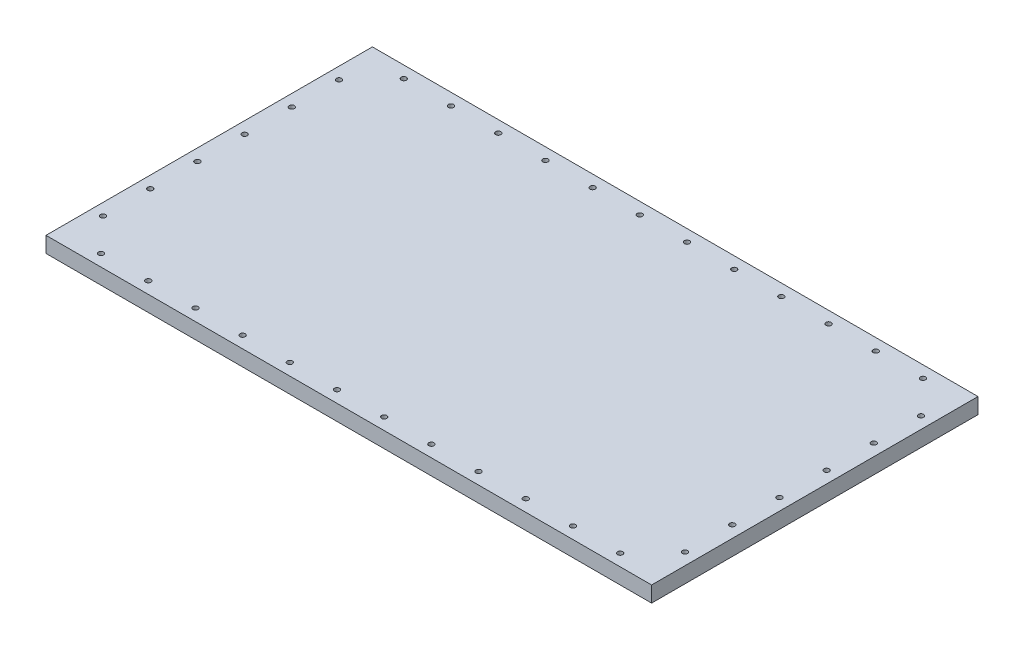
SolidWorks part; units mm, degrees
ref_plane "Front Plane" through (0, 0, 0) normal (0, 0, 1) x (1, 0, 0)
ref_plane "Top Plane" through (0, 0, 0) normal (0, 1, 0) x (1, 0, 0)
ref_plane "Right Plane" through (0, 0, 0) normal (1, 0, 0) x (0, 0, -1)
sketch "Sketch1" plane through (0, 0, 0) normal (0, 0, 1) x (1, 0, 0)
  line L1 (495.3, -12.7) -> (-495.3, -12.7)
  line L2 (495.3, -12.7) -> (495.3, 12.7)
  line L3 (495.3, 12.7) -> (-495.3, 12.7)
  line L4 (-495.3, -12.7) -> (-495.3, 12.7)
  line L5 (495.3, -12.7) -> (-495.3, 12.7) construction
  line L6 (495.3, 12.7) -> (-495.3, -12.7) construction
  line L7 (-495.3, -12.7) -> (-488.95, -12.7)
  line L8 (-495.3, -12.7) -> (-495.3, 12.7)
  line L9 (-495.3, 12.7) -> (-488.95, 12.7)
  line L10 (-488.95, -12.7) -> (-488.95, 12.7)
  line L12 (495.3, -12.7) -> (488.95, -12.7)
  line L13 (495.3, -12.7) -> (495.3, 12.7)
  line L14 (495.3, 12.7) -> (488.95, 12.7)
  line L15 (488.95, -12.7) -> (488.95, 12.7)
  point P0 (0, 0)
  dimension "D1" = 25.4
  dimension "D2" = 990.6
  dimension "D3" = 25.4
  dimension "D4" = 6.35
  dimension "D5" = 6.35
  dimension "D6" = 25.4
extrude "Boss-Extrude1" add sketch "Sketch1" along normal blind 527.05 contours L1 L15 L14 L2 L3 L4 L9 L10
hole_wizard "CSK for 5/16 Flat Head Machine Screw3" positions "Sketch14" profile "Sketch15" countersink size "5/16" standard "ANSI Inch" end condition through all
sketch "Sketch14" plane through (0, -12.7, 0) normal (0, -1, 0) x (-1, 0, 0)
  line L0 (-488.95, -527.05) -> (488.95, -527.05) construction
  line L3 (-488.95, 0) -> (488.95, 0) construction
  line L4 (-488.95, -527.05) -> (-488.95, 0) construction
  line L7 (488.95, -527.05) -> (488.95, 0) construction
  point P0 (419.1, -508)
  point P10 (342.9, -508)
  point P11 (266.7, -508)
  point P12 (190.5, -508)
  point P13 (114.3, -508)
  point P14 (38.1, -508)
  point P15 (-38.1, -508)
  point P16 (-114.3, -508)
  point P17 (-190.5, -508)
  point P18 (-266.7, -508)
  point P35 (419.1, -19.05)
  point P36 (342.9, -19.05)
  point P37 (266.7, -19.05)
  point P38 (190.5, -19.05)
  point P39 (114.3, -19.05)
  point P40 (38.1, -19.05)
  point P41 (-38.1, -19.05)
  point P42 (-114.3, -19.05)
  point P43 (-190.5, -19.05)
  point P44 (-266.7, -19.05)
  point P51 (-342.9, -508)
  point P52 (-342.9, -19.05)
  point P53 (-419.1, -508)
  point P54 (-419.1, -19.05)
  dimension "D1" = 19.05
  dimension "D2" = 76.2
  dimension "D4" = 3
  dimension "D6" = 19.05
  dimension "D7" = 69.85
  dimension "D8" = 69.85
  dimension "D3" = 10
  dimension "D5" = 2
sketch "Sketch15" plane through (-419.1, -12.7, 508) normal (1, 0, 0) x (0, 0, -1)
  line L0 (0, 0) -> (0, 25.4)
  line L1 (0, 25.4) -> (4.2164, 25.4)
  line L2 (4.2164, 25.4) -> (4.2164, 4.4267)
  line L3 (4.2164, 4.4267) -> (8.0645, 0)
  line L5 (8.0645, 0) -> (0, 0)
  line L6 (-4.2164, 4.4267) -> (-8.0645, 0) construction
  line L11 (0, -6.35) -> (0, 107.95) construction
  dimension "Thru Hole Dia." = 8.4328
  dimension "Thru Hole Depth" = 25.4
  dimension "Near C'Sink Dia." = 16.129
  dimension "Near C'Sink Angle" = 82
hole_wizard "CSK for 5/16 Flat Head Machine Screw4" positions "Sketch16" profile "Sketch17" countersink size "5/16" standard "ANSI Inch" end condition through all
sketch "Sketch16" plane through (0, -12.7, 0) normal (0, -1, 0) x (-1, 0, 0)
  line L0 (-488.95, -527.05) -> (488.95, -527.05) construction
  line L1 (-488.95, 0) -> (488.95, 0) construction
  line L5 (488.95, -527.05) -> (488.95, 0) construction
  line L6 (-488.95, -527.05) -> (-488.95, 0) construction
  point P0 (469.9, -454.025)
  point P10 (469.9, -377.825)
  point P11 (469.9, -301.625)
  point P12 (469.9, -225.425)
  point P13 (469.9, -149.225)
  point P14 (469.9, -73.025)
  point P33 (-469.9, -454.025)
  point P34 (-469.9, -377.825)
  point P35 (-469.9, -301.625)
  point P36 (-469.9, -225.425)
  point P37 (-469.9, -149.225)
  point P38 (-469.9, -73.025)
  dimension "D1" = 73.025
  dimension "D3" = 73.025
  dimension "D4" = 19.05
  dimension "D6" = 19.05
  dimension "D2" = 6
  dimension "D5" = 2
sketch "Sketch17" plane through (-469.9, -12.7, 454.025) normal (1, 0, 0) x (0, 0, -1)
  line L0 (0, 0) -> (0, 25.4)
  line L1 (0, 25.4) -> (4.2164, 25.4)
  line L2 (4.2164, 25.4) -> (4.2164, 4.4267)
  line L3 (4.2164, 4.4267) -> (8.0645, 0)
  line L5 (8.0645, 0) -> (0, 0)
  line L6 (-4.2164, 4.4267) -> (-8.0645, 0) construction
  line L11 (0, -6.35) -> (0, 107.95) construction
  dimension "Thru Hole Dia." = 8.4328
  dimension "Thru Hole Depth" = 25.4
  dimension "Near C'Sink Dia." = 16.129
  dimension "Near C'Sink Angle" = 82
